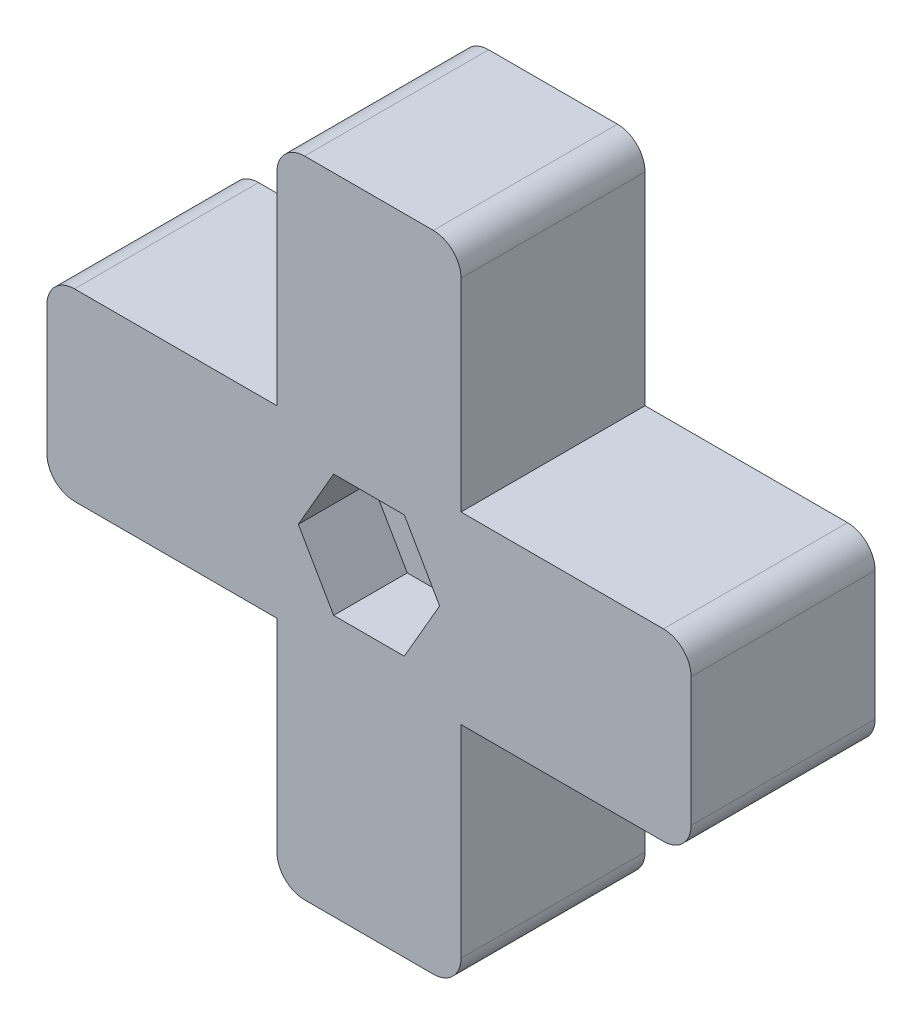
SolidWorks part; units mm, degrees
ref_plane "Plan de face" through (0, 0, 0) normal (0, 0, 1) x (1, 0, 0)
ref_plane "Plan de dessus" through (0, 0, 0) normal (0, 1, 0) x (1, 0, 0)
ref_plane "Plan de droite" through (0, 0, 0) normal (1, 0, 0) x (0, 0, -1)
sketch "Esquisse1" plane through (0, 0, 0) normal (0, 0, 1) x (1, 0, 0)
  line L1 (0, 0) -> (70, 0)
  line L2 (0, 0) -> (0, 20)
  line L3 (0, 20) -> (70, 20)
  line L4 (70, 0) -> (70, 20)
  line L5 (45, 45) -> (25, 45)
  line L6 (45, 45) -> (45, -25)
  line L7 (45, -25) -> (25, -25)
  line L8 (25, 45) -> (25, -25)
  point P9 (21.6061, -24.4204)
  point P10 (35, 45)
  point P11 (35, 20)
  point P12 (45, 10)
  point P13 (70, 10)
  dimension "D1" = 20
  dimension "D2" = 70
extrude "Boss.-Extru.1" add sketch "Esquisse1" along normal blind 20 contours L5 L8 L3 L6 | L3 L8 L1 L6 | L8 L3 L2 L1 | L1 L8 L7 L6 | L3 L6 L1 L4
sketch "Esquisse2" plane through (0, 0, 20) normal (0, 0, 1) x (1, 0, 0)
  line L2 (45, 45) -> (25, 45) construction
  line L3 (70, 0) -> (70, 20) construction
  circle A0 centre (35, 10) radius 4.05
  point P2 (0, 0)
  point P5 (35, 45)
  point P6 (0, 0)
  point P9 (70, 10)
  dimension "D1" = 8.1
extrude "Enlèv. mat.-Extru.1" cut sketch "Esquisse2" against normal up to next contours A0
sketch "Esquisse4" plane through (0, 0, 20) normal (0, 0, 1) x (1, 0, 0)
  line L1 (27.3212, 10) -> (31.1606, 3.35)
  line L2 (31.1606, 3.35) -> (38.8394, 3.35)
  line L3 (38.8394, 3.35) -> (42.6788, 10)
  line L4 (42.6788, 10) -> (38.8394, 16.65)
  line L5 (38.8394, 16.65) -> (31.1606, 16.65)
  line L6 (31.1606, 16.65) -> (27.3212, 10)
  circle A0 centre (35, 10) radius 6.65 construction
  dimension "D1" = 13.3
extrude "Enlèv. mat.-Extru.3" cut sketch "Esquisse4" against normal blind 8
fillet "Congé1" radius 3 8 edges at (70, 20, 10) (70, 0, 10) (0, 0, 10) (0, 20, 10) (45, 45, 10) (45, -25, 10) (25, -25, 10) (25, 45, 10)
